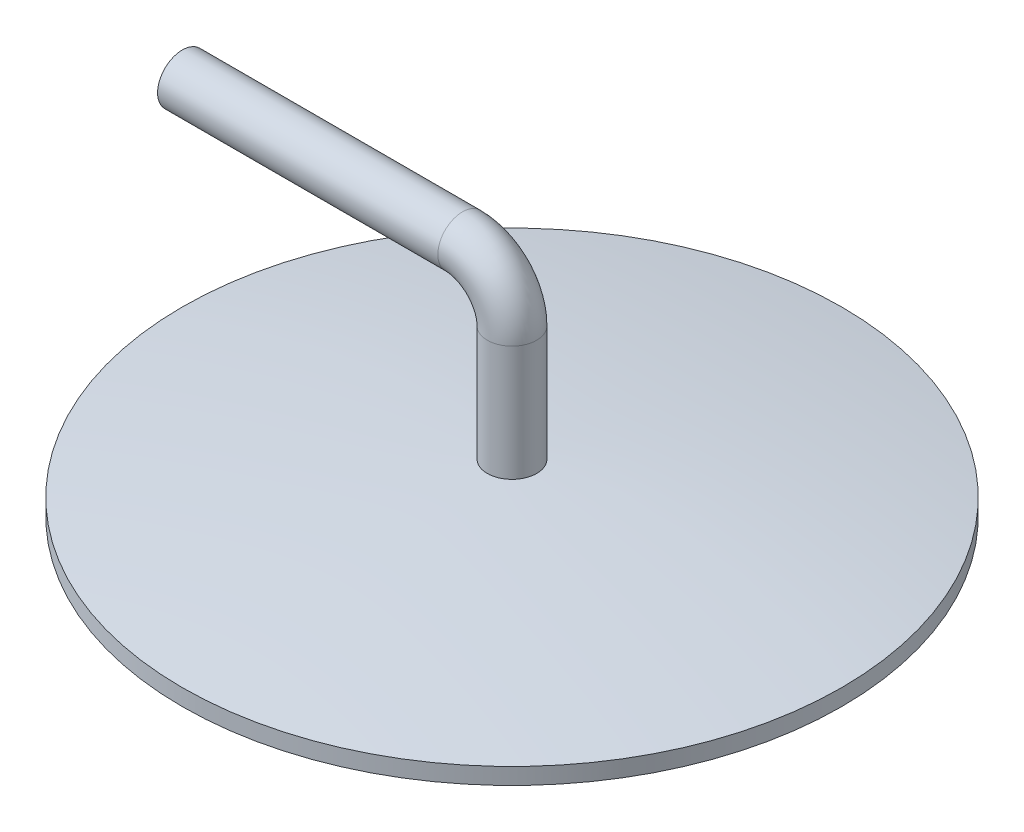
SolidWorks part; units mm, degrees
material "Zinc AC41A Alloy, As Cast"
ref_plane "Front Plane" through (0, 0, 0) normal (0, 0, 1) x (1, 0, 0)
ref_plane "Top Plane" through (0, 0, 0) normal (0, 1, 0) x (1, 0, 0)
ref_plane "Right Plane" through (0, 0, 0) normal (1, 0, 0) x (0, 0, -1)
sketch "Sketch1" plane through (0, 0, 0) normal (1, 0, 0) x (0, 0, -1)
  line L0 (0, 30) -> (-15, 30)
  line L1 (0, 0) -> (-200, 0)
  line L2 (0, 0) -> (0, 30)
  line L3 (0, 30) -> (-15, 30)
  line L4 (-200, 0) -> (-200, 10)
  line L5 (-200, 0) -> (-200, 10)
  line L6 (0, 30) -> (0, -55.371) construction
  arc A0 (-15, 30) -> (-200, 10) centre (41.1194, -1354.7295) ccw
  dimension "D1" = 30
  dimension "D2" = 200
  dimension "D3" = 15
  dimension "D4" = 10
revolve "Revolve2" add sketch "Sketch1" angle 360 about L6
sketch "Sketch2" plane through (0, 30, 0) normal (0, 1, 0) x (1, 0, 0)
  circle A0 centre (0, 0) radius 10
  circle A1 centre (0, 0) radius 15
  circle A2 centre (0, 0) radius 15
  dimension "D1" = 0
  dimension "D2" = 5
sketch "Sketch3" plane through (0, 0, 0) normal (0, 0, 1) x (1, 0, 0)
  line L0 (0, 30) -> (0, 100)
  line L1 (-30, 130) -> (-200, 130)
  arc A0 (-30, 130) -> (0, 100) centre (-30, 100) cw
  point P7 (0, 130)
  dimension "D3" = 30
  dimension "D1" = 200
  dimension "D2" = 100
sweep "Sweep1" add profiles "Sketch2" path "Sketch3"
